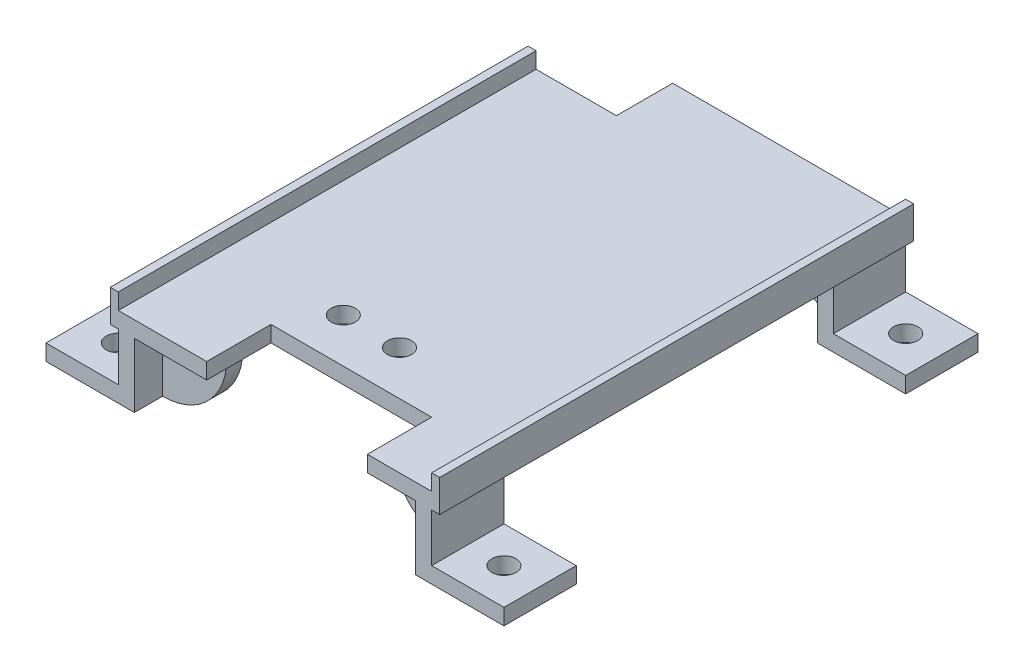
SolidWorks part; units mm, degrees
ref_plane "Front Plane" through (0, 0, 0) normal (0, 0, 1) x (1, 0, 0)
ref_plane "Top Plane" through (0, 0, 0) normal (0, 1, 0) x (1, 0, 0)
ref_plane "Right Plane" through (0, 0, 0) normal (1, 0, 0) x (0, 0, -1)
sketch "Sketch1" plane through (0, 0, 0) normal (0, 1, 0) x (1, 0, 0)
  line L1 (0, 0) -> (57, 0)
  line L2 (0, 0) -> (0, 59)
  line L3 (0, 59) -> (57, 59)
  line L4 (57, 0) -> (57, 59)
  dimension "D1" = 57
  dimension "D2" = 59
extrude "Boss-Extrude1" add sketch "Sketch1" along normal blind 10
sketch "Sketch2" plane through (57, 0, 0) normal (1, 0, 0) x (0, 0, -1)
  line L0 (0, 10) -> (59, 10) construction
  line L1 (9, 10) -> (50, 10)
  line L2 (9, 10) -> (9, 0)
  line L3 (9, 0) -> (50, 0)
  line L4 (50, 10) -> (50, 0)
  line L5 (0, 0) -> (59, 0) construction
  line L6 (0, 10) -> (0, 0) construction
  dimension "D1" = 9
  dimension "D2" = 9
extrude "Cut-Extrude1" cut sketch "Sketch2" against normal blind 9
sketch "Sketch4" plane through (0, 10, 0) normal (0, 1, 0) x (1, 0, 0)
  line L0 (0, 59) -> (0, 0) construction
  line L1 (0, 52) -> (10, 52)
  line L2 (0, 52) -> (0, 59)
  line L3 (0, 59) -> (10, 59)
  line L4 (10, 52) -> (10, 59)
  line L5 (57, 59) -> (0, 59) construction
  dimension "D1" = 10
  dimension "D2" = 7
extrude "Cut-Extrude3" cut sketch "Sketch4" against normal through all
sketch "Sketch5" plane through (0, 0, 0) normal (-1, 0, 0) x (0, 0, 1)
  line L0 (-52, 10) -> (0, 10) construction
  line L1 (-43, 10) -> (-9, 10)
  line L2 (-43, 10) -> (-43, 0)
  line L3 (-43, 0) -> (-9, 0)
  line L4 (-9, 10) -> (-9, 0)
  line L5 (-52, 0) -> (0, 0) construction
  line L6 (-52, 0) -> (-52, 10) construction
  line L7 (0, 10) -> (0, 0) construction
  dimension "D1" = 9
  dimension "D2" = 9
extrude "Cut-Extrude4" cut sketch "Sketch5" against normal blind 9
sketch "Sketch6" plane through (0, 10, 0) normal (0, 1, 0) x (1, 0, 0)
  line L0 (0, 0) -> (57, 0) construction
  line L1 (9, 0) -> (48, 0)
  line L2 (9, 0) -> (9, 59)
  line L3 (9, 59) -> (48, 59)
  line L4 (48, 0) -> (48, 59)
  line L5 (57, 59) -> (10, 59) construction
sketch "Sketch7" plane through (0, 0, 0) normal (0, 0, 1) x (1, 0, 0)
  line L0 (0, 0) -> (57, 0) construction
  line L1 (9, 10) -> (48, 10)
  line L2 (9, 10) -> (9, 0)
  line L3 (9, 0) -> (48, 0)
  line L4 (48, 10) -> (48, 0)
sketch "Sketch8" plane through (0, 0, 0) normal (0, 0, 1) x (1, 0, 0)
  line L0 (9, 10) -> (48, 10) construction
  line L1 (20, 10) -> (40, 10)
  line L2 (20, 10) -> (20, 0)
  line L3 (20, 0) -> (40, 0)
  line L4 (40, 10) -> (40, 0)
  line L5 (9, 0) -> (48, 0) construction
  line L6 (9, 10) -> (9, 0) construction
  point P8 (20, 5)
  dimension "D1" = 11
  dimension "D2" = 20
extrude "Cut-Extrude5" cut sketch "Sketch8" against normal blind 8
sketch "Sketch9" plane through (0, 0, 0) normal (0, -1, 0) x (-1, 0, 0)
  line L0 (-57, 59) -> (-10, 59) construction
  line L1 (-11, 0) -> (-46, 0)
  line L2 (-11, 0) -> (-11, 59)
  line L3 (-11, 59) -> (-46, 59)
  line L4 (-46, 0) -> (-46, 59)
  dimension "D1" = 35
  dimension "D2" = 2
extrude "Cut-Extrude6" cut sketch "Sketch9" against normal blind 8
sketch "Sketch10" plane through (0, 10, 0) normal (0, 1, 0) x (1, 0, 0)
  line L1 (10, 52) -> (19, 52)
  line L2 (10, 52) -> (10, 59)
  line L3 (10, 59) -> (19, 59)
  line L4 (19, 52) -> (19, 59)
  dimension "D1" = 9
extrude "Cut-Extrude7" cut sketch "Sketch10" against normal through all
sketch "Sketch11" plane through (0, 10, 0) normal (0, 1, 0) x (1, 0, 0)
  line L1 (48, 0) -> (57, 0)
  line L2 (48, 0) -> (48, 9)
  line L3 (48, 9) -> (57, 9)
  line L4 (57, 0) -> (57, 9)
extrude "Cut-Extrude8" cut sketch "Sketch11" against normal blind 8
sketch "Sketch12" plane through (0, 10, 0) normal (0, 1, 0) x (1, 0, 0)
  line L1 (48, 59) -> (57, 59)
  line L2 (48, 59) -> (48, 50)
  line L3 (48, 50) -> (57, 50)
  line L4 (57, 59) -> (57, 50)
extrude "Cut-Extrude9" cut sketch "Sketch12" against normal blind 8
sketch "Sketch13" plane through (0, 10, 0) normal (0, 1, 0) x (1, 0, 0)
  line L1 (0, 52) -> (9, 52)
  line L2 (0, 52) -> (0, 43)
  line L3 (0, 43) -> (9, 43)
  line L4 (9, 52) -> (9, 43)
extrude "Cut-Extrude10" cut sketch "Sketch13" against normal blind 8
sketch "Sketch14" plane through (0, 10, 0) normal (0, 1, 0) x (1, 0, 0)
  line L1 (9, 0) -> (0, 0)
  line L2 (9, 0) -> (9, 9)
  line L3 (9, 9) -> (0, 9)
  line L4 (0, 0) -> (0, 9)
extrude "Cut-Extrude11" cut sketch "Sketch14" against normal blind 8
sketch "Sketch15" plane through (0, 0, 0) normal (0, -1, 0) x (-1, 0, 0)
  line L0 (-46, 59) -> (-46, 0) construction
  line L1 (-48, 9) -> (-46, 9)
  line L2 (-48, 9) -> (-48, 50)
  line L3 (-48, 50) -> (-46, 50)
  line L4 (-46, 9) -> (-46, 50)
extrude "Cut-Extrude12" cut sketch "Sketch15" against normal blind 8
sketch "Sketch16" plane through (0, 0, 0) normal (0, -1, 0) x (-1, 0, 0)
  line L0 (-11, 0) -> (-11, 52) construction
  line L1 (-9, 9) -> (-11, 9)
  line L2 (-9, 9) -> (-9, 43)
  line L3 (-9, 43) -> (-11, 43)
  line L4 (-11, 9) -> (-11, 43)
extrude "Cut-Extrude13" cut sketch "Sketch16" against normal blind 8
sketch "Sketch31" plane through (11, 0, 0) normal (1, 0, 0) x (0, 0, -1)
  line L0 (0, 8) -> (9, 8) construction
  line L1 (3.5, 8) -> (5.5, 8)
  line L2 (3.5, 8) -> (3.5, 0)
  line L3 (3.5, 0) -> (5.5, 0)
  line L4 (5.5, 8) -> (5.5, 0)
  line L5 (0, 0) -> (9, 0) construction
  line L6 (0, 8) -> (0, 0) construction
  line L7 (9, 8) -> (9, 0) construction
  point P10 (0, 4)
  dimension "D1" = 3.5
  dimension "D2" = 3.5
revolve "Revolve3" add sketch "Sketch31" angle 90 about L1
sketch "Sketch32" plane through (11, 0, 0) normal (1, 0, 0) x (0, 0, -1)
  line L0 (43, 8) -> (52, 8) construction
  line L1 (46.5, 8) -> (48.5, 8)
  line L2 (46.5, 8) -> (46.5, 0)
  line L3 (46.5, 0) -> (48.5, 0)
  line L4 (48.5, 8) -> (48.5, 0)
  line L5 (43, 0) -> (52, 0) construction
  line L6 (43, 8) -> (43, 0) construction
  line L7 (52, 0) -> (52, 8) construction
  dimension "D1" = 3.5
  dimension "D2" = 3.5
revolve "Revolve4" add sketch "Sketch32" angle 90 about L1
sketch "Sketch33" plane through (0, 8, 0) normal (0, -1, 0) x (1, 0, 0)
  line L0 (40, 0) -> (40, -8) construction
  line L1 (40, -3.5) -> (46, -3.5)
  line L2 (40, -3.5) -> (40, -5.5)
  line L3 (40, -5.5) -> (46, -5.5)
  line L4 (46, -3.5) -> (46, -5.5)
  line L5 (46, -9) -> (46, 0) construction
  line L6 (46, 0) -> (40, 0) construction
  dimension "D1" = 3.5
  dimension "D2" = 3.5
revolve "Revolve5" add sketch "Sketch33" angle 90 about L4
sketch "Sketch34" plane through (46, 0, 0) normal (-1, 0, 0) x (0, 0, 1)
  line L0 (-59, 0) -> (-50, 0) construction
  line L1 (-53.5, 0) -> (-55.5, 0)
  line L2 (-53.5, 0) -> (-53.5, 8)
  line L3 (-53.5, 8) -> (-55.5, 8)
  line L4 (-55.5, 0) -> (-55.5, 8)
  line L5 (-59, 8) -> (-50, 8) construction
  line L6 (-50, 8) -> (-50, 0) construction
  line L7 (-59, 8) -> (-59, 0) construction
  point P10 (-55.5, 4)
  dimension "D1" = 3.5
  dimension "D2" = 3.5
revolve "Revolve6" add sketch "Sketch34" angle 90 about L3
sketch "Sketch41" plane through (0, 2, 0) normal (0, 1, 0) x (1, 0, 0)
  line L0 (57, 0) -> (57, 9) construction
  line L1 (48, 0) -> (57, 0) construction
  line L2 (48, 50) -> (57, 50) construction
  line L3 (57, 50) -> (57, 59) construction
  line L4 (0, 43) -> (9, 43) construction
  line L5 (0, 0) -> (9, 0) construction
  line L6 (0, 9) -> (0, 0) construction
  line L7 (0, 52) -> (0, 43) construction
  circle A0 centre (52.5, 4.5) radius 1.5
  circle A1 centre (52.5, 54.5) radius 1.5
  circle A2 centre (4.5, 4.5) radius 1.5
  circle A3 centre (4.5, 47.5) radius 1.5
  point P4 (57, 4.5)
  dimension "D3" = 3
  dimension "D6" = 3
  dimension "D7" = 3
  dimension "D8" = 3
  dimension "D1" = 4.5
  dimension "D2" = 4.5
  dimension "D4" = 4.5
  dimension "D5" = 4.5
  dimension "D9" = 4.5
  dimension "D10" = 4.5
  dimension "D11" = 4.5
  dimension "D12" = 4.5
extrude "Cut-Extrude14" cut sketch "Sketch41" against normal through all
sketch "Sketch42" plane through (0, 10, 0) normal (0, 1, 0) x (1, 0, 0)
  line L0 (9, 0) -> (9, 52) construction
  line L1 (48, 59) -> (48, 0) construction
  line L2 (48, 59) -> (19, 59) construction
  circle A0 centre (23.5, 13.5) radius 1.5
  circle A1 centre (30.5, 13.5) radius 1.5
  dimension "D5" = 3
  dimension "D6" = 3
  dimension "D1" = 14.5
  dimension "D2" = 17.5
  dimension "D3" = 45.5
  dimension "D4" = 45.5
extrude "Cut-Extrude15" cut sketch "Sketch42" against normal through all
sketch "Sketch46" plane through (48, 0, 0) normal (1, 0, 0) x (0, 0, -1)
  line L0 (59, 2) -> (59, 10) construction
  line L1 (0, 10) -> (59, 10)
  line L2 (0, 10) -> (0, 8)
  line L3 (0, 8) -> (59, 8)
  line L4 (59, 10) -> (59, 8)
extrude "Boss-Extrude3" add sketch "Sketch46" along normal blind 1
sketch "Sketch47" plane through (0, 10, 0) normal (0, 1, 0) x (1, 0, 0)
  line L0 (40, 0) -> (49, 0) construction
  line L1 (49, 59) -> (48, 59)
  line L2 (49, 59) -> (49, 0)
  line L3 (49, 0) -> (48, 0)
  line L4 (48, 59) -> (48, 0)
  dimension "D1" = 1
extrude "Boss-Extrude4" add sketch "Sketch47" along normal blind 2
sketch "Sketch48" plane through (9, 0, 0) normal (-1, 0, 0) x (0, 0, 1)
  line L1 (-52, 10) -> (0, 10)
  line L2 (-52, 10) -> (-52, 8)
  line L3 (-52, 8) -> (0, 8)
  line L4 (0, 10) -> (0, 8)
extrude "Boss-Extrude5" add sketch "Sketch48" along normal blind 1
sketch "Sketch49" plane through (0, 10, 0) normal (0, 1, 0) x (1, 0, 0)
  line L0 (8, 0) -> (20, 0) construction
  line L1 (8, 52) -> (9, 52)
  line L2 (8, 52) -> (8, 0)
  line L3 (8, 0) -> (9, 0)
  line L4 (9, 52) -> (9, 0)
  dimension "D1" = 1
extrude "Boss-Extrude6" add sketch "Sketch49" along normal blind 2
